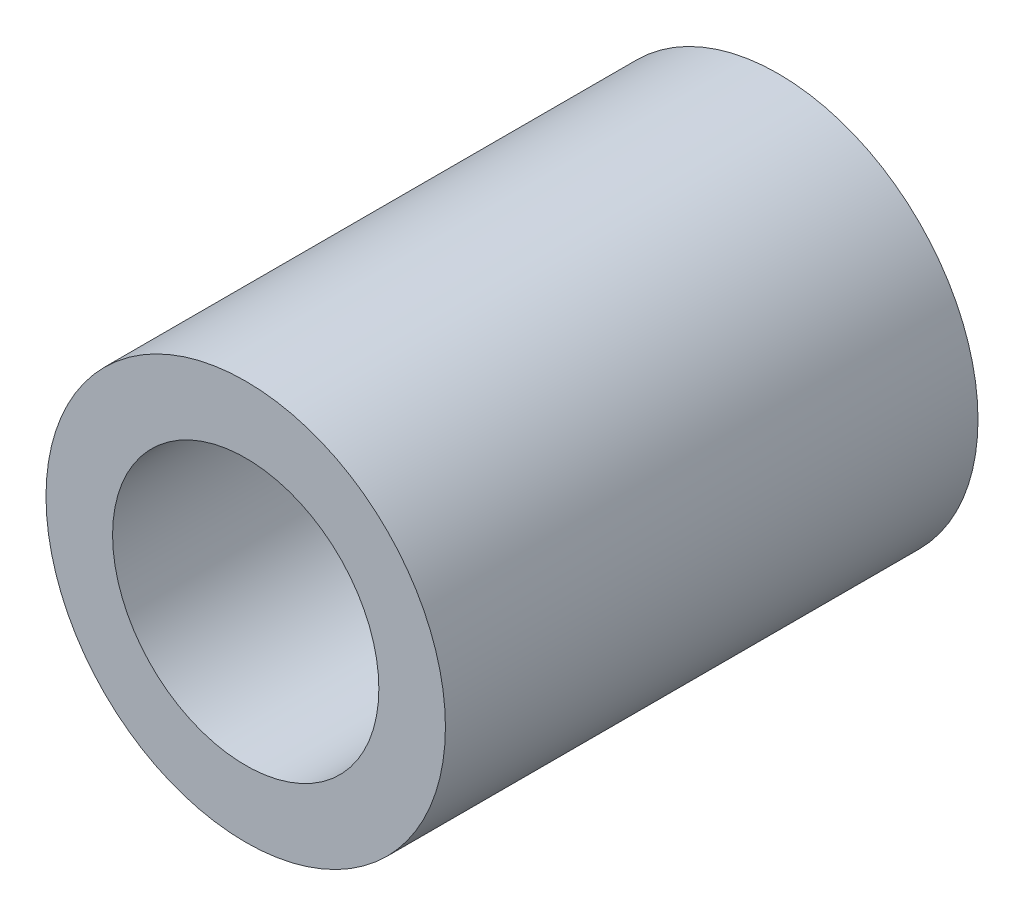
SolidWorks part; units mm, degrees
material "黄銅"
ref_plane "正面" through (0, 0, 0) normal (0, 0, 1) x (1, 0, 0)
ref_plane "平面" through (0, 0, 0) normal (0, 1, 0) x (1, 0, 0)
ref_plane "右側面" through (0, 0, 0) normal (1, 0, 0) x (0, 0, -1)
sketch "ｽｹｯﾁ1" plane through (0, 0, 0) normal (0, 0, 1) x (1, 0, 0)
  circle A0 centre (0, 0) radius 3
  dimension "D1" = 6
extrude "ﾎﾞｽ - 押し出し1" add sketch "ｽｹｯﾁ1" along normal blind 8
sketch "ｽｹｯﾁ2" plane through (0, 0, 8) normal (0, 0, 1) x (1, 0, 0)
  circle A0 centre (0, 0) radius 2
  dimension "D1" = 4
extrude "ｶｯﾄ - 押し出し1" cut sketch "ｽｹｯﾁ2" against normal through all
